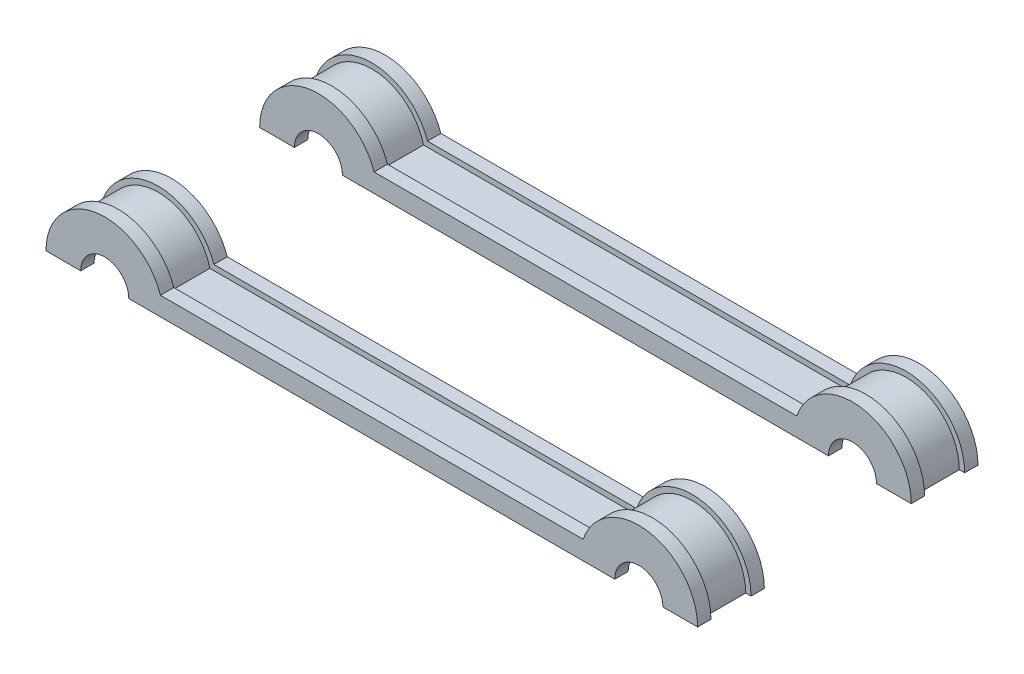
SolidWorks part; units mm, degrees
ref_plane "Front Plane" through (0, 0, 0) normal (0, 0, 1) x (1, 0, 0)
ref_plane "Top Plane" through (0, 0, 0) normal (0, 1, 0) x (1, 0, 0)
ref_plane "Right Plane" through (0, 0, 0) normal (1, 0, 0) x (0, 0, -1)
sketch "Sketch2" plane through (0, 0, 0) normal (0, 0, 1) x (1, 0, 0)
  line L0 (-17, 0) -> (-20, 0)
  line L1 (17, 0) -> (20, 0)
  line L2 (183, 0) -> (180, 0)
  line L3 (217, 0) -> (220, 0)
  line L4 (20, 0) -> (180, 0)
  line L5 (19.3649, 5) -> (180.6351, 5)
  arc A0 (-17, 0) -> (17, 0) centre (0, 0) cw
  arc A1 (183, 0) -> (217, 0) centre (200, 0) cw
  arc A2 (-20, 0) -> (20, 0) centre (0, 0) cw
  arc A3 (180, 0) -> (220, 0) centre (200, 0) cw
  dimension "D1" = 17
  dimension "D2" = 200
  dimension "D4" = 5
  dimension "D3" = 3
extrude "Boss-Extrude1" add sketch "Sketch2" along normal mid plane 95 contours A2 L0 A0 L1 | L4 A3 L5 A2
sketch "Sketch4" plane through (0, 0, 47.5) normal (0, 0, 1) x (1, 0, 0)
  line L0 (217, 0) -> (209, 0)
  line L1 (183, 0) -> (191, 0)
  line L2 (17, 0) -> (9, 0)
  line L3 (-17, 0) -> (-9, 0)
  line L4 (-20, 0) -> (-17, 0)
  line L5 (17, 0) -> (183, 0)
  line L6 (217, 0) -> (220, 0)
  line L7 (180.6351, 5) -> (19.3649, 5)
  line L8 (-20, 0) -> (-17, 0)
  line L9 (17, 0) -> (183, 0)
  line L10 (217, 0) -> (220, 0)
  line L11 (180.6351, 5) -> (19.3649, 5)
  line L12 (179.1433, 7) -> (20.8567, 7)
  line L13 (220, 0) -> (222, 0)
  line L14 (-20, 0) -> (-22, 0)
  arc A0 (209, 0) -> (191, 0) centre (200, 0) ccw
  arc A1 (9, 0) -> (-9, 0) centre (0, 0) ccw
  arc A2 (222, 0) -> (179.1433, 7) centre (200, 0) ccw
  arc A3 (20.8567, 7) -> (-22, 0) centre (0, 0) ccw
  arc A4 (19.3649, 5) -> (-20, 0) centre (0, 0) ccw
  arc A5 (17, 0) -> (-17, 0) centre (0, 0) ccw
  arc A6 (217, 0) -> (183, 0) centre (200, 0) ccw
  arc A7 (220, 0) -> (180.6351, 5) centre (200, 0) ccw
  arc A8 (19.3649, 5) -> (-20, 0) centre (0, 0) ccw
  arc A9 (17, 0) -> (-17, 0) centre (0, 0) ccw
  arc A10 (217, 0) -> (183, 0) centre (200, 0) ccw
  arc A11 (220, 0) -> (180.6351, 5) centre (200, 0) ccw
  arc M9 (19.3649, 5) -> (-20, 0) centre (0, 0) ccw
  line M10 (-20, 0) -> (-17, 0)
  arc M11 (-17, 0) -> (17, 0) centre (0, 0) cw
  line M12 (17, 0) -> (183, 0)
  arc M13 (183, 0) -> (217, 0) centre (200, 0) cw
  line M14 (217, 0) -> (220, 0)
  arc M15 (220, 0) -> (180.6351, 5) centre (200, 0) ccw
  line M16 (180.6351, 5) -> (19.3649, 5)
  dimension "D1" = 0
  dimension "D2" = 8
  dimension "D3" = 2
sketch "Sketch3" plane through (0, 0, 0) normal (1, 0, 0) x (0, 0, -1)
  line L1 (47.5, -500) -> (-32.5, -500)
  line L2 (47.5, -500) -> (47.5, 500)
  line L3 (47.5, 500) -> (-32.5, 500)
  line L4 (-32.5, -500) -> (-32.5, 500)
  line L5 (47.5, -500) -> (-32.5, 500) construction
  line L6 (47.5, 500) -> (-32.5, -500) construction
  line L7 (-47.5, 20) -> (-47.5, 0) construction
  line L8 (47.5, 0) -> (47.5, 20) construction
  point P9 (0, 0)
  dimension "D1" = 1000
  dimension "D2" = 15
extrude "Cut-Extrude1" cut sketch "Sketch3" against normal through all both and the other way through all
extrude "Boss-Extrude2" add sketch "Sketch4" along normal blind 5 contours L12 A3 L14 L13 A2 M9 M16 M15 | M16 M9 M10 M11 M12 M13 M14 M15 | A1 L2 L3 M11 | A0 L0 L1 M13
ref_plane "Plane1" through (0, 0, 40) normal (0, 0, -1) x (-1, 0, 0)
mirror "Mirror1" about plane through (0, 0, 40) normal (0, 0, -1) of "Boss-Extrude2"
mirror "Mirror4" about plane through (0, 0, 0) normal (0, 0, 1) of bodies 105
